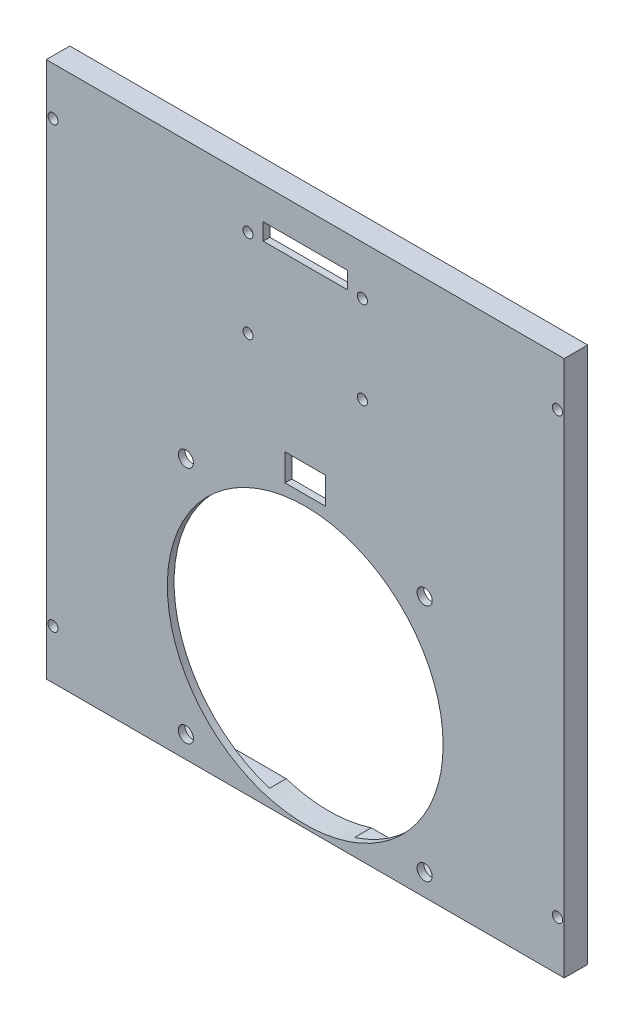
SolidWorks part; units mm, degrees
ref_plane "Piano frontale" through (0, 0, 0) normal (0, 0, 1) x (1, 0, 0)
ref_plane "Piano superiore" through (0, 0, 0) normal (0, 1, 0) x (1, 0, 0)
ref_plane "Piano destro" through (0, 0, 0) normal (1, 0, 0) x (0, 0, -1)
sketch "Schizzo1" plane through (0, 0, 0) normal (0, 0, 1) x (1, 0, 0)
  line L0 (-75, 80) -> (-75, -80) construction
  line L1 (77, -80) -> (-77, -80)
  line L2 (77, -80) -> (77, 80)
  line L3 (77, 80) -> (-77, 80)
  line L4 (-77, -80) -> (-77, 80)
  line L5 (77, -80) -> (-77, 80) construction
  line L6 (77, 80) -> (-77, -80) construction
  line L7 (0, 0) -> (-77, 0) construction
  line L8 (0, 0) -> (0, 80) construction
  circle A1 centre (-75, 65.3439) radius 1.5
  circle A2 centre (75, 65.3439) radius 1.5
  circle A3 centre (75, -65.3439) radius 1.5
  circle A4 centre (-75, -65.3439) radius 1.5
  point P0 (0, 0)
  dimension "D4" = 3
  dimension "D1" = 154
  dimension "D2" = 160
  dimension "D3" = 4
  dimension "D5" = 14.6561
extrude "Estrusione-Estrusione1" add sketch "Schizzo1" along normal blind 7
sketch "Schizzo2" plane through (0, 0, 0) normal (0, 0, -1) x (-1, 0, 0)
  line L0 (32, -38) -> (0, -38) construction
  line L1 (0, -38) -> (0, 3) construction
  line L2 (0, -38) -> (35.5, -2.5) construction
  line L10 (0, -80) -> (0, 80) construction
  line L11 (77, -80) -> (-77, -80) construction
  line L12 (-77, 80) -> (77, 80) construction
  line L13 (0, -38) -> (0, 10) construction
  line L15 (-6, 6) -> (6, 6)
  line L20 (-6, 6) -> (-6, 14)
  line L21 (-6, 14) -> (6, 14)
  line L22 (6, 6) -> (6, 14)
  line L23 (-6, 6) -> (6, 14) construction
  line L24 (-6, 14) -> (6, 6) construction
  circle A0 centre (0, -38) radius 41
  circle A1 centre (35.5, -2.5) radius 2.25
  circle A2 centre (35.5, -73.5) radius 2.25
  circle A3 centre (-35.5, -2.5) radius 2.25
  circle A4 centre (-35.5, -73.5) radius 2.25
  dimension "D2" = 4.5
  dimension "D7" = 82
  dimension "D9" = 8
  dimension "D10" = 12
  dimension "D1" = 45
  dimension "D3" = 0
  dimension "D4" = 42
  dimension "D5" = 32
  dimension "D6" = 50.2046
  dimension "D8" = 48
extrude "Taglio-Estrusione1" cut sketch "Schizzo2" against normal blind 10
sketch "Schizzo3" plane through (0, 0, 0) normal (0, 0, -1) x (-1, 0, 0)
  line L0 (0, 80) -> (0, 14) construction
  line L1 (-77, 80) -> (77, 80) construction
  line L2 (6, 14) -> (-6, 14) construction
  line L3 (0, 65) -> (17, 65) construction
  line L4 (17, 65) -> (17, 39) construction
  line L5 (12.5, 65) -> (-12.5, 65)
  line L9 (12.5, 65) -> (12.5, 70)
  line L10 (12.5, 70) -> (-12.5, 70)
  line L11 (-12.5, 70) -> (-12.5, 65)
  circle A0 centre (17, 65) radius 1.5
  circle A1 centre (17, 39) radius 1.5
  circle A2 centre (-17, 39) radius 1.5
  circle A3 centre (-17, 65) radius 1.5
  point P18 (0, 65)
  dimension "D3" = 3
  dimension "D5" = 3
  dimension "D1" = 15
  dimension "D2" = 17
  dimension "D4" = 26
  dimension "D6" = 25
  dimension "D7" = 5
extrude "Taglio-Estrusione2" cut sketch "Schizzo3" against normal blind 10
sketch "Schizzo4" plane through (0, 0, 0) normal (0, 0, -1) x (-1, 0, 0)
  line L0 (0, 3) -> (0, 80) construction
  line L1 (-77, 80) -> (77, 80) construction
  line L2 (17, 39) -> (-17, 39) construction
  line L3 (0, 37) -> (8, 37) construction
  circle A0 centre (0, -38) radius 41 construction
  circle A1 centre (8, 37) radius 1.5
  circle A2 centre (8, 37) radius 3
  circle A3 centre (-8, 37) radius 3
  circle A4 centre (-8, 37) radius 1.5
  dimension "D2" = 3
  dimension "D4" = 6
  dimension "D1" = 8
  dimension "D3" = 2
sketch "Schizzo5" plane through (0, 0, 0) normal (0, 0, -1) x (-1, 0, 0)
  line L0 (77, 80) -> (77, 77) construction
  line L3 (77, 80) -> (77, -80) construction
  line L4 (77, 77) -> (70, 77) construction
  line L5 (-77, -80) -> (-77, -77) construction
  line L6 (-77, -80) -> (-77, 80) construction
  line L7 (-77, -77) -> (-70, -77) construction
  line L9 (70, 77) -> (-70, 77)
  line L10 (70, 77) -> (70, -77)
  line L11 (70, -77) -> (-70, -77)
  line L12 (-70, 77) -> (-70, -77)
  dimension "D1" = 3
  dimension "D2" = 7
  dimension "D3" = 3
  dimension "D4" = 7
extrude "Taglio-Estrusione3" cut sketch "Schizzo5" against normal blind 5
sketch "Schizzo6" plane through (0, 0, 5) normal (0, 0, -1) x (-1, 0, 0)
  line L0 (0, 80) -> (0, 3) construction
  circle A0 centre (8, 37) radius 3
  circle A1 centre (8, 37) radius 1.5
  circle A2 centre (-8, 37) radius 1.5
  circle A3 centre (-8, 37) radius 3
extrude "Estrusione-Estrusione2" add sketch "Schizzo6" along normal blind 3
fillet "Raccordo1" radius 2 2 edges at (11, 37, 5) (-5, 37, 5)
sketch "Schizzo8" plane through (0, 80, 0) normal (0, 1, 0) x (1, 0, 0)
  line L1 (-77, -7) -> (77, -7)
  line L2 (-77, -7) -> (-77, 0)
  line L3 (-77, 0) -> (77, 0)
  line L4 (77, -7) -> (77, 0)
extrude "Taglio-Estrusione4" cut sketch "Schizzo8" against normal blind 0.5
